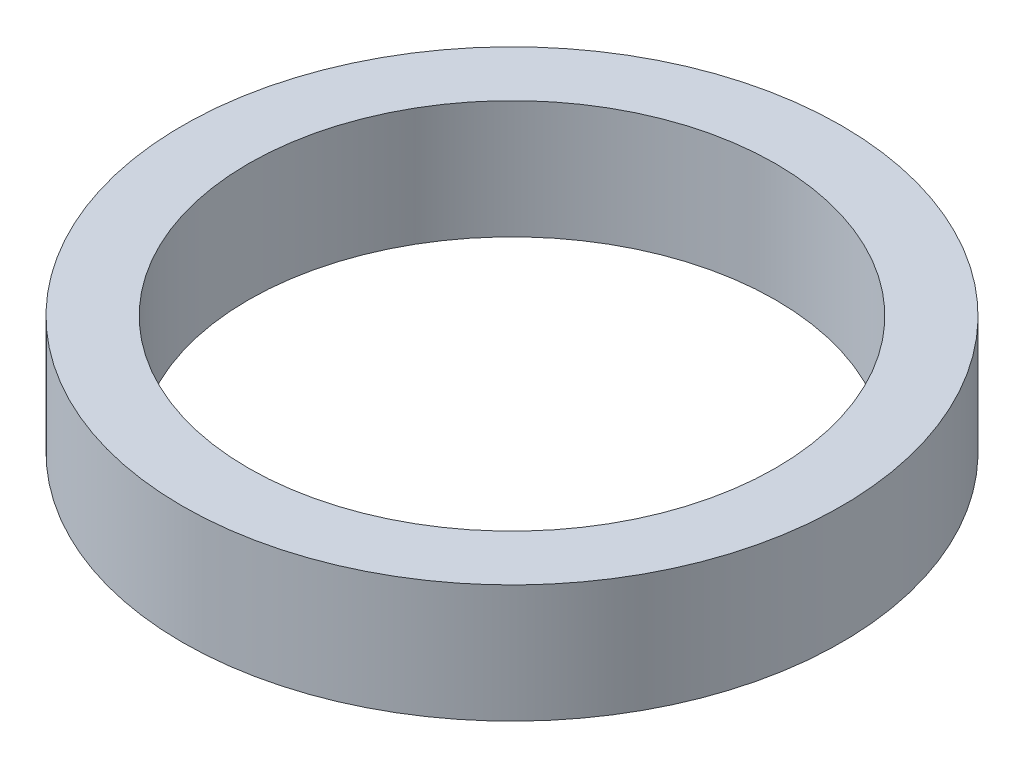
SolidWorks part; units mm, degrees
material "Epoxy, Unfilled"
ref_plane "Front Plane" through (0, 0, 0) normal (0, 0, 1) x (1, 0, 0)
ref_plane "Top Plane" through (0, 0, 0) normal (0, 1, 0) x (1, 0, 0)
ref_plane "Right Plane" through (0, 0, 0) normal (1, 0, 0) x (0, 0, -1)
sketch "Sketch2" plane through (0, 0, 0) normal (0, 1, 0) x (1, 0, 0)
  circle A0 centre (0, 0) radius 9.525
  dimension "D1" = 19.05
extrude "Boss-Extrude1" add sketch "Sketch2" along normal blind 3.41
sketch "Sketch3" plane through (0, 0, 0) normal (0, -1, 0) x (1, 0, 0)
  circle A0 centre (0, 0) radius 7.62
  point P0 (0, 0)
  dimension "D1" = 15.24
extrude "Cut-Extrude1" cut sketch "Sketch3" against normal through all contours A0
